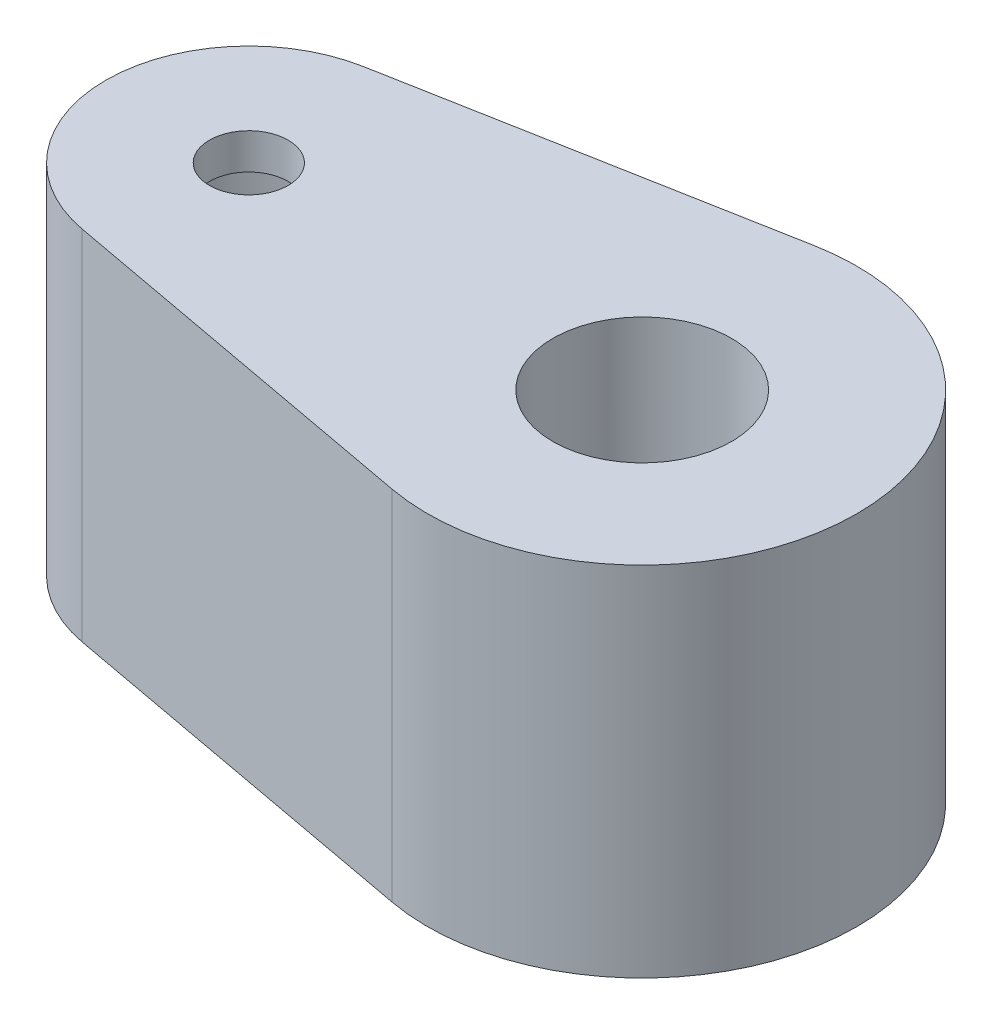
SolidWorks part; units mm, degrees
ref_plane "Спереди" through (0, 0, 0) normal (0, 0, 1) x (1, 0, 0)
ref_plane "Сверху" through (0, 0, 0) normal (0, 1, 0) x (1, 0, 0)
ref_plane "Справа" through (0, 0, 0) normal (1, 0, 0) x (0, 0, -1)
sketch "Эскиз1" plane through (0, 0, 0) normal (0, 1, 0) x (1, 0, 0)
  circle A0 centre (0, 0) radius 1.5
  circle A1 centre (0, 0) radius 1.1
  dimension "D1" = 3
  dimension "D2" = 2.2
extrude "Бобышка-Вытянуть1" add sketch "Эскиз1" along normal blind 6.5
sketch "Эскиз2" plane through (0, 0, 0) normal (0, -1, 0) x (1, 0, 0)
  circle A0 centre (0, 0) radius 4
  circle A1 centre (0, 0) radius 1.1 construction
  circle A2 centre (0, 0) radius 1.1
  dimension "D1" = 8
extrude "Бобышка-Вытянуть2" add sketch "Эскиз2" along normal blind 1
sketch "Эскиз3" plane through (0, -1, 0) normal (0, -1, 0) x (1, 0, 0)
  circle A0 centre (0, 0) radius 3.25
  circle A1 centre (0, 0) radius 4 construction
  circle A2 centre (0, 0) radius 4
  dimension "D1" = 6.5
extrude "Бобышка-Вытянуть3" add sketch "Эскиз3" along normal blind 9
sketch "Эскиз4" plane through (0, 0, 0) normal (0, 1, 0) x (1, 0, 0)
  line L0 (9.9091, 5.9) -> (-0.7273, 3.9333)
  line L1 (0, 0) -> (11, 0)
  line L2 (-0.7273, -3.9333) -> (9.9091, -5.9)
  circle A0 centre (11, 0) radius 2.5
  circle A1 centre (11, 0) radius 6
  circle A2 centre (0, 0) radius 4 construction
  circle A4 centre (0, 0) radius 4
  circle A5 centre (0, 0) radius 4
  dimension "D2" = 5
  dimension "D3" = 12
  dimension "D1" = 11
  dimension "D4" = 0
extrude "Бобышка-Вытянуть4" add sketch "Эскиз4" against normal up to surface (10 mm away)
sketch "Эскиз5" plane through (0, -10, 0) normal (0, -1, 0) x (1, 0, 0)
  circle A0 centre (11, 0) radius 4.5
  dimension "D1" = 9
extrude "Вырез-Вытянуть1" cut sketch "Эскиз5" against normal blind 3
sketch "Эскиз7" plane through (0, 6.5, 0) normal (0, 1, 0) x (1, 0, 0)
  circle A1 centre (0, 0) radius 1.5
  circle A2 centre (0, 0) radius 1.5
  dimension "D1" = 0
extrude "Вырез-Вытянуть2" cut sketch "Эскиз7" against normal up to surface (6.5 mm away) up to face at (0, 0, 1.5)
